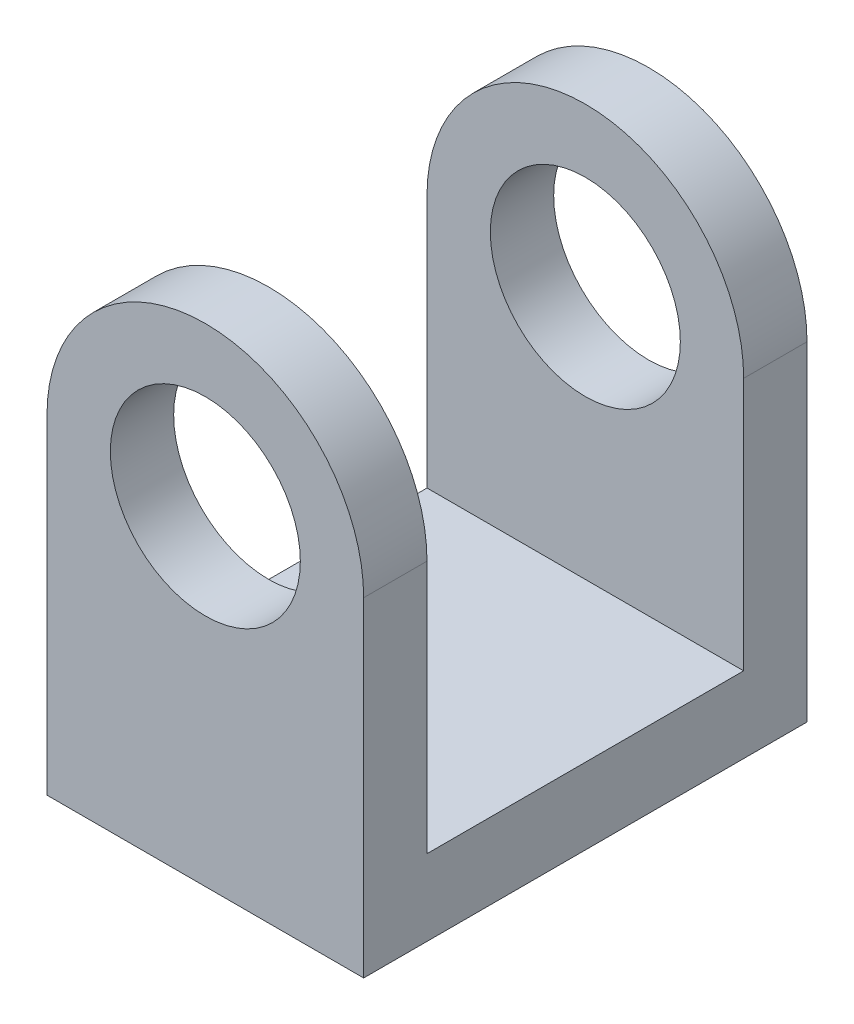
SolidWorks part; units mm, degrees
ref_plane "Front Plane" through (0, 0, 0) normal (0, 0, 1) x (1, 0, 0)
ref_plane "Top Plane" through (0, 0, 0) normal (0, 1, 0) x (1, 0, 0)
ref_plane "Right Plane" through (0, 0, 0) normal (1, 0, 0) x (0, 0, -1)
ref_plane "Plane1" through (0, 0, 30) normal (0, 0, 1) x (1, 0, 0)
sketch "Sketch2" plane through (0, 0, 30) normal (0, 0, 1) x (1, 0, 0)
  line L2 (-25, 22.5) -> (-25, -22.5)
  line L3 (-25, -22.5) -> (25, -22.5)
  line L4 (25, 22.5) -> (25, -22.5)
  line L5 (-25, 22.5) -> (25, -22.5) construction
  line L6 (-25, -22.5) -> (25, 22.5) construction
  arc A0 (-25, 22.5) -> (25, 22.5) centre (0, 22.5) cw
  circle A1 centre (0, 22.5) radius 15
  point P0 (0, 0)
  dimension "D3" = 30
  dimension "D1" = 50
  dimension "D2" = 45
extrude "Boss-Extrude2" add sketch "Sketch2" along normal mid plane 10
sketch "Sketch3" plane through (0, 0, 25) normal (0, 0, -1) x (-1, 0, 0)
  line L0 (25, 22.5) -> (25, -22.5) construction
  line L1 (-25, -22.5) -> (25, -22.5)
  line L2 (-25, -22.5) -> (-25, -17.5)
  line L3 (-25, -17.5) -> (25, -17.5)
  line L4 (25, -22.5) -> (25, -17.5)
  dimension "D1" = 5
extrude "Boss-Extrude3" add sketch "Sketch3" along normal blind 60
mirror "Mirror3" about plane through (0, 0, 0) normal (0, 0, 1) of "Boss-Extrude2"
sketch "Sketch4" plane through (0, -22.5, 0) normal (0, -1, 0) x (1, 0, 0)
  circle A1 centre (0, 0) radius 10
  dimension "D1" = 20
extrude "Boss-Extrude4" add sketch "Sketch4" along normal blind 15
sketch "Sketch5" plane through (0, -22.5, 0) normal (0, -1, 0) x (1, 0, 0)
  line L4 (-25, 35) -> (-25, -35)
  line L5 (-25, -35) -> (25, -35)
  line L6 (25, -35) -> (25, 35)
  line L7 (25, 35) -> (-25, 35)
  line L8 (-25, 35) -> (-25, -35)
  line L9 (-25, -35) -> (25, -35)
  line L10 (25, -35) -> (25, 35)
  line L11 (25, 35) -> (-25, 35)
  circle A1 centre (0, 0) radius 15
  dimension "D2" = 30
  dimension "D1" = 0
extrude "Boss-Extrude5" add sketch "Sketch5" along normal blind 7
